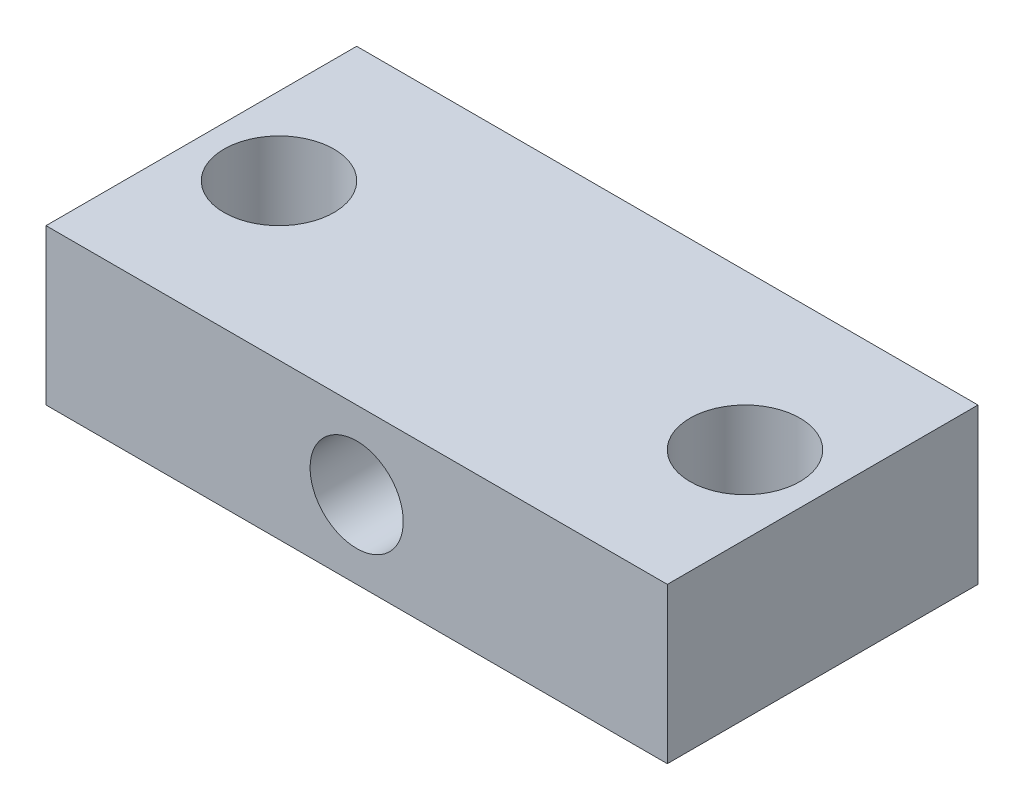
SolidWorks part; units mm, degrees
ref_plane "Front Plane" through (0, 0, 0) normal (0, 0, 1) x (1, 0, 0)
ref_plane "Top Plane" through (0, 0, 0) normal (0, 1, 0) x (1, 0, 0)
ref_plane "Right Plane" through (0, 0, 0) normal (1, 0, 0) x (0, 0, -1)
sketch "Sketch1" plane through (0, 0, 0) normal (0, 1, 0) x (1, 0, 0)
  line L1 (-12.7, -6.35) -> (12.7, -6.35)
  line L2 (-12.7, -6.35) -> (-12.7, 6.35)
  line L3 (-12.7, 6.35) -> (12.7, 6.35)
  line L4 (12.7, -6.35) -> (12.7, 6.35)
  line L5 (-12.7, -6.35) -> (12.7, 6.35) construction
  line L6 (-12.7, 6.35) -> (12.7, -6.35) construction
  point P0 (0, 0)
  dimension "D1" = 25.4
  dimension "D2" = 12.7
extrude "Boss-Extrude1" add sketch "Sketch1" along normal blind 6.35
sketch "Sketch2" plane through (0, 0, -6.35) normal (0, 0, -1) x (-1, 0, 0)
  line L0 (-12.7, 6.35) -> (-12.7, 0) construction
  circle A0 centre (0, 3.175) radius 1.905
  point P2 (0, 0)
  point P3 (-12.7, 3.175)
  dimension "D1" = 3.81
extrude "Cut-Extrude1" cut sketch "Sketch2" against normal through all contours A0
hole_wizard "#8 Clearance Hole1" positions "Sketch3" profile "Sketch4" hole size "#8" standard "ANSI Inch" end condition through all
sketch "Sketch3" plane through (0, 6.35, 0) normal (0, 1, 0) x (1, 0, 0)
  line L0 (-9.525, 0) -> (9.525, 0) construction
  point P1 (-9.525, 0)
  point P2 (9.525, 0)
  point P6 (0, 0)
  point P8 (-9.525, 0)
  point P12 (9.525, 0)
  dimension "D1" = 19.05
sketch "Sketch4" plane through (9.525, 6.35, 0) normal (1, 0, 0) x (0, 0, 1)
  line L0 (0, 0) -> (0, 6.35)
  line L1 (0, 6.35) -> (2.2479, 6.35)
  line L2 (2.2479, 6.35) -> (2.2479, 0)
  line L5 (2.2479, 0) -> (0, 0)
  line L11 (0, -6.35) -> (0, 107.95) construction
  dimension "Thru Hole Dia." = 4.4958
  dimension "Thru Hole Depth" = 6.35
